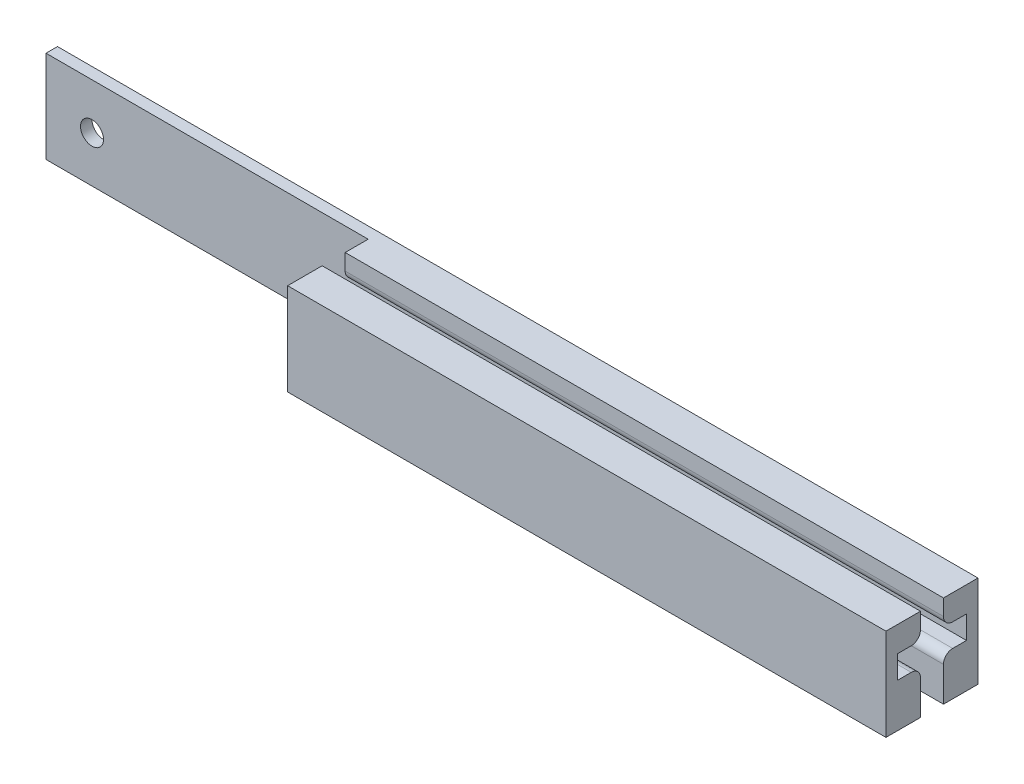
SolidWorks part; units mm, degrees
ref_plane "Front Plane" through (0, 0, 0) normal (0, 0, 1) x (1, 0, 0)
ref_plane "Top Plane" through (0, 0, 0) normal (0, 1, 0) x (1, 0, 0)
ref_plane "Right Plane" through (0, 0, 0) normal (1, 0, 0) x (0, 0, -1)
sketch "Sketch1" plane through (0, 0, 0) normal (1, 0, 0) x (0, 0, -1)
  line L1 (0, 0) -> (-100, 0)
  line L2 (0, 0) -> (0, 100)
  line L3 (0, 100) -> (-100, 100)
  line L4 (-100, 0) -> (-100, 100)
  line L5 (-62.5, 100) -> (-37.5, 100)
  line L6 (-62.5, 100) -> (-62.5, 20)
  line L7 (-62.5, 20) -> (-37.5, 20)
  line L8 (-37.5, 100) -> (-37.5, 20)
  line L9 (-62.5, 100) -> (-37.5, 20) construction
  line L10 (-62.5, 20) -> (-37.5, 100) construction
  line L11 (-87.5, 72.5) -> (-62.5, 72.5)
  line L12 (-87.5, 72.5) -> (-87.5, 47.5)
  line L13 (-87.5, 47.5) -> (-62.5, 47.5)
  line L14 (-62.5, 72.5) -> (-62.5, 47.5)
  line L15 (-87.5, 72.5) -> (-62.5, 47.5) construction
  line L16 (-87.5, 47.5) -> (-62.5, 72.5) construction
  line L17 (-37.5, 72.5) -> (-12.5, 72.5)
  line L18 (-37.5, 72.5) -> (-37.5, 47.5)
  line L19 (-37.5, 47.5) -> (-12.5, 47.5)
  line L20 (-12.5, 72.5) -> (-12.5, 47.5)
  line L21 (-37.5, 72.5) -> (-12.5, 47.5) construction
  line L22 (-37.5, 47.5) -> (-12.5, 72.5) construction
  point P5 (-50, 60)
  point P10 (-75, 60)
  point P15 (-25, 60)
  dimension "D1" = 100
  dimension "D2" = 100
  dimension "D3" = 50
  dimension "D4" = 25
  dimension "D5" = 40
  dimension "D6" = 80
  dimension "D7" = 25
  dimension "D8" = 25
  dimension "D9" = 0
  dimension "D10" = 0
extrude "Boss-Extrude1" add sketch "Sketch1" along normal blind 650 contours L17 L20 L19 L8 L7 L6 L13 L12 L11 L3 L4 L1 L2
sketch "Sketch2" plane through (0, 0, 0) normal (0, -1, 0) x (1, 0, 0)
  line L1 (50, 62.5) -> (750, 62.5)
  line L2 (50, 62.5) -> (50, 37.5)
  line L3 (50, 37.5) -> (750, 37.5)
  line L4 (750, 62.5) -> (750, 37.5)
  dimension "D1" = 37.5
  dimension "D2" = 25
  dimension "D3" = 50
  dimension "D4" = 700
extrude "Cut-Extrude1" cut sketch "Sketch2" against normal blind 800
fillet "Fillet1" radius 10 4 edges at (325, 72.5, 62.5) (325, 47.5, 62.5) (325, 72.5, 37.5) (325, 47.5, 37.5)
sketch "Sketch3" plane through (0, 0, 0) normal (-1, 0, 0) x (0, 0, 1)
  line L0 (0, 100) -> (37.5, 100) construction
  line L1 (0, 0) -> (12.5, 0)
  line L2 (0, 0) -> (0, 100)
  line L3 (0, 100) -> (12.5, 100)
  line L4 (12.5, 0) -> (12.5, 100)
  line L5 (12.5, 72.5) -> (12.5, 47.5) construction
  dimension "D1" = 12.5
extrude "Boss-Extrude2" add sketch "Sketch3" along normal blind 350
sketch "Sketch4" plane through (0, 0, 12.5) normal (0, 0, 1) x (1, 0, 0)
  line L0 (-350, 100) -> (0, 100) construction
  circle A0 centre (-300, 50) radius 12.5
  dimension "D2" = 25
  dimension "D1" = 300
  dimension "D3" = 50
extrude "Cut-Extrude2" cut sketch "Sketch4" against normal blind 350
